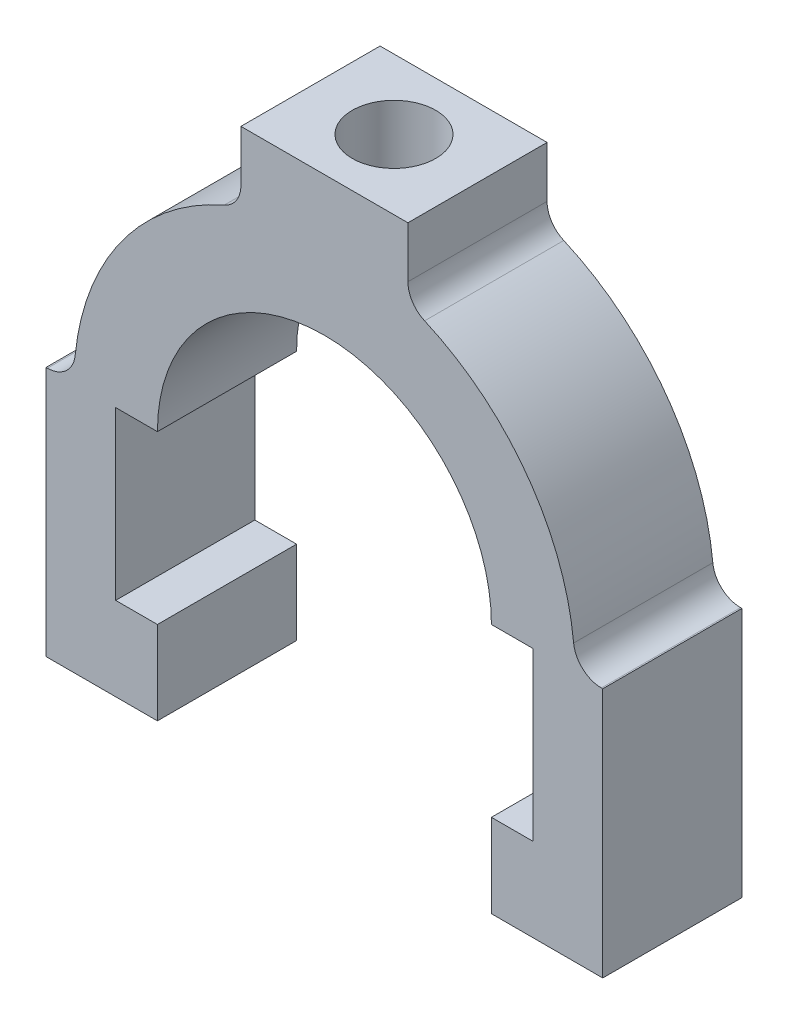
SolidWorks part; units mm, degrees
ref_plane "Front Plane" through (0, 0, 0) normal (0, 0, 1) x (1, 0, 0)
ref_plane "Top Plane" through (0, 0, 0) normal (0, 1, 0) x (1, 0, 0)
ref_plane "Right Plane" through (0, 0, 0) normal (1, 0, 0) x (0, 0, -1)
sketch "Sketch1" plane through (0, 0, 0) normal (0, 0, 1) x (1, 0, 0)
  line L0 (0, 0) -> (0, 36)
  line L1 (0, 0) -> (-16, 0)
  line L2 (-16, 0) -> (-16, 12)
  line L3 (-16, 12) -> (-10, 12)
  line L4 (-10, 12) -> (-10, 36)
  line L5 (-10, 36) -> (-16, 36)
  line L6 (0, 36) -> (-0.2005, 36)
  line L7 (-52, 80) -> (-28, 80)
  line L8 (-28, 72.6606) -> (-28, 80)
  line L9 (-52, 72.6606) -> (-52, 80)
  line L10 (-40, 36) -> (-40, 4.4753) construction
  line L11 (-80, 36) -> (-79.7995, 36)
  line L12 (-70, 36) -> (-64, 36)
  line L13 (-70, 12) -> (-70, 36)
  line L14 (-64, 12) -> (-70, 12)
  line L15 (-64, 0) -> (-64, 12)
  line L16 (-80, 0) -> (-64, 0)
  line L17 (-80, 0) -> (-80, 36)
  arc A0 (-16, 36) -> (-64, 36) centre (-40, 36) ccw
  arc A1 (-4.1805, 39.6) -> (-25.6, 68.9945) centre (-40, 36) ccw
  arc A2 (-0.2005, 36) -> (-4.1805, 39.6) centre (-0.2005, 40) cw
  arc A3 (-54.4, 68.9945) -> (-75.8195, 39.6) centre (-40, 36) ccw
  arc A4 (-25.6, 68.9945) -> (-28, 72.6606) centre (-24, 72.6606) cw
  arc A5 (-54.4, 68.9945) -> (-52, 72.6606) centre (-56, 72.6606) ccw
  arc A6 (-79.7995, 36) -> (-75.8195, 39.6) centre (-79.7995, 40) ccw
  point P24 (-40, 80)
  dimension "D5" = 24
  dimension "D6" = 36
  dimension "D7" = 4
  dimension "D8" = 4
  dimension "D1" = 16
  dimension "D2" = 36
  dimension "D3" = 12
  dimension "D4" = 10
  dimension "D9" = 80
  dimension "D10" = 24
  dimension "D11" = 7.3394
extrude "Boss-Extrude1" add sketch "Sketch1" along normal blind 20 contours A1 A4 L8 L7 L9 A5 A3 A6 L11 L17 L16 L15 L14 L13 L12 A0 L5 L4 L3 L2 L1 L0 L6 A2
sketch "Sketch2" plane through (0, 80, 0) normal (0, 1, 0) x (1, 0, 0)
  line L0 (-52, 0) -> (-28, 0) construction
  circle A0 centre (-40, -10) radius 6
  dimension "D1" = 12
  dimension "D2" = 12
  dimension "D3" = 10
extrude "Cut-Extrude2" cut sketch "Sketch2" against normal through all
